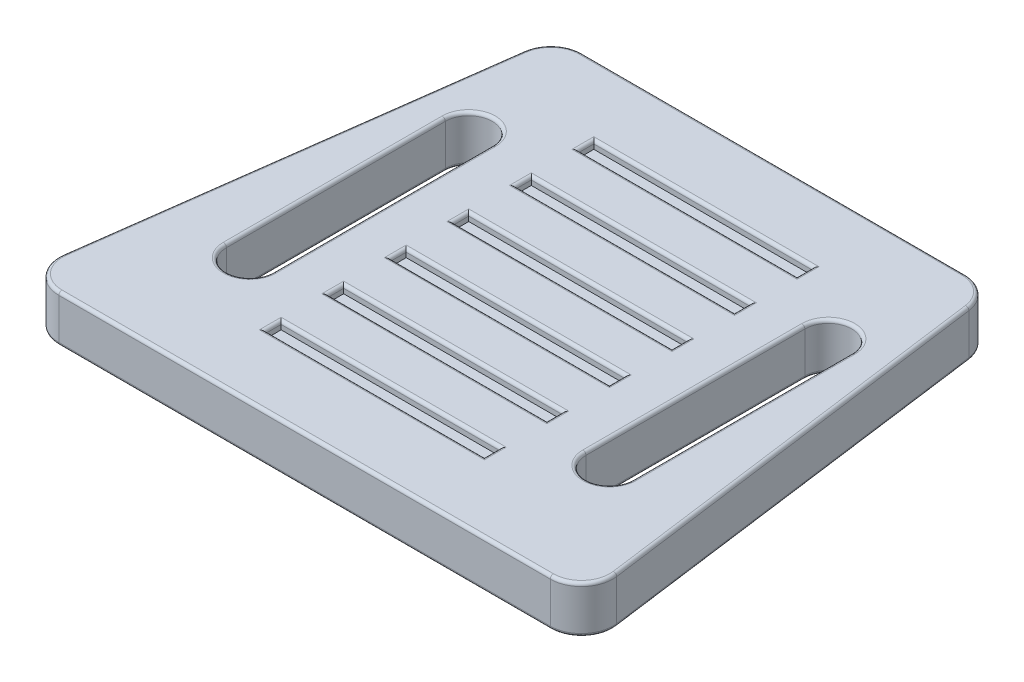
SolidWorks part; units mm, degrees
ref_plane "Front Plane" through (0, 0, 0) normal (0, 0, 1) x (1, 0, 0)
ref_plane "Top Plane" through (0, 0, 0) normal (0, 1, 0) x (1, 0, 0)
ref_plane "Right Plane" through (0, 0, 0) normal (1, 0, 0) x (0, 0, -1)
sketch "Sketch1" plane through (0, 0, 0) normal (0, 1, 0) x (1, 0, 0)
  line L0 (0, 0) -> (0, 30) construction
  line L1 (15.7156, 0) -> (-15.7156, 0)
  line L2 (-17.6981, 2.2643) -> (-14.2314, 28.2643)
  line L3 (-12.249, 30) -> (12.249, 30)
  line L4 (-11.5, 22) -> (-11.5, 8) construction
  line L5 (-10, 22) -> (-10, 8)
  line L6 (-13, 22) -> (-13, 8)
  line L7 (17.6981, 2.2643) -> (14.2314, 28.2643)
  line L8 (11.5, 22) -> (11.5, 8) construction
  line L9 (10, 22) -> (10, 8)
  line L10 (13, 22) -> (13, 8)
  arc A0 (-10, 22) -> (-13, 22) centre (-11.5, 22) ccw
  arc A1 (-13, 8) -> (-10, 8) centre (-11.5, 8) ccw
  arc A2 (-15.7156, 0) -> (-17.6981, 2.2643) centre (-15.7156, 2) cw
  arc A3 (-14.2314, 28.2643) -> (-12.249, 30) centre (-12.249, 28) cw
  arc A4 (15.7156, 0) -> (17.6981, 2.2643) centre (15.7156, 2) ccw
  arc A5 (14.2314, 28.2643) -> (12.249, 30) centre (12.249, 28) ccw
  arc A6 (10, 22) -> (13, 22) centre (11.5, 22) cw
  arc A7 (13, 8) -> (10, 8) centre (11.5, 8) cw
  point P7 (-11.5, 15)
  point P14 (-18, 0)
  point P17 (-14, 30)
  point P26 (11.5, 15)
  dimension "D7" = 14
  dimension "D8" = 2
  dimension "D1" = 3
  dimension "D2" = 18
  dimension "D3" = 30
  dimension "D4" = 14
  dimension "D5" = 8
  dimension "D6" = 10
extrude "Boss-Extrude1" add sketch "Sketch1" along normal blind 3
ref_plane "Plane1" through (0, 0, -22) normal (0, 0, 1) x (0, -1, 0)
sketch "Sketch2" plane through (0, 3, 0) normal (0, 1, 0) x (1, 0, 0)
  line L0 (0, -1.65) -> (0, 1.65) construction
  line L1 (-7, 5.5) -> (7, 5.5)
  line L2 (-7, 5.5) -> (-7, 4.5)
  line L3 (-7, 4.5) -> (7, 4.5)
  line L4 (7, 5.5) -> (7, 4.5)
  line L5 (-7, 8.5) -> (7, 8.5)
  line L6 (7, 9.5) -> (7, 8.5)
  line L7 (-7, 9.5) -> (7, 9.5)
  line L8 (-7, 9.5) -> (-7, 8.5)
  line L9 (-7, 12.5) -> (7, 12.5)
  line L10 (7, 13.5) -> (7, 12.5)
  line L11 (-7, 13.5) -> (7, 13.5)
  line L12 (-7, 13.5) -> (-7, 12.5)
  line L13 (-7, 16.5) -> (7, 16.5)
  line L14 (7, 17.5) -> (7, 16.5)
  line L15 (-7, 17.5) -> (7, 17.5)
  line L16 (-7, 17.5) -> (-7, 16.5)
  line L17 (-7, 20.5) -> (7, 20.5)
  line L18 (7, 21.5) -> (7, 20.5)
  line L19 (-7, 21.5) -> (7, 21.5)
  line L20 (-7, 21.5) -> (-7, 20.5)
  line L21 (-7, 24.5) -> (7, 24.5)
  line L22 (7, 25.5) -> (7, 24.5)
  line L23 (-7, 25.5) -> (7, 25.5)
  line L24 (-7, 25.5) -> (-7, 24.5)
  dimension "D1" = 14
  dimension "D2" = 7
  dimension "D3" = 1
  dimension "D4" = 4.5
  dimension "D6" = 3
  dimension "D5" = 6
extrude "Cut-Extrude1" cut sketch "Sketch2" against normal blind 0.5
fillet "Fillet1" radius 0.2 56 edges at (11.5, 0, -6.5) (10, 0, -15) (11.5, 0, -23.5) (13, 0, -15) (-11.5, 0, -6.5) (-13, 0, -15) (-11.5, 0, -23.5) (-10, 0, -15) (0, 0, 0) (0, 0, -30) (-15.9648, 0, -15.2643) (10, 3, -15) (11.5, 3, -6.5) (13, 3, -15) (11.5, 3, -23.5) (-15.9648, 3, -15.2643) (0, 3, -30) (0, 3, 0) (-13, 3, -15) (-11.5, 3, -6.5) (-10, 3, -15) (-11.5, 3, -23.5) (17.2204, 0, -0.6826) (15.9648, 0, -15.2643) (13.5664, 0, -29.5048) (-13.5664, 0, -29.5048) (-17.2204, 0, -0.6826) (-13.5664, 3, -29.5048) (13.5664, 3, -29.5048) (15.9648, 3, -15.2643) (17.2204, 3, -0.6826) (-17.2204, 3, -0.6826) (7, 3, -5) (0, 3, -5.5) (-7, 3, -5) (0, 3, -4.5) (7, 3, -9) (0, 3, -9.5) (-7, 3, -9) (0, 3, -8.5) (7, 3, -13) (0, 3, -13.5) (-7, 3, -13) (0, 3, -12.5) (7, 3, -17) (0, 3, -17.5) (-7, 3, -17) (0, 3, -16.5) (7, 3, -21) (0, 3, -21.5) (-7, 3, -21) (0, 3, -20.5) (7, 3, -25) (0, 3, -25.5) (-7, 3, -25) (0, 3, -24.5)
